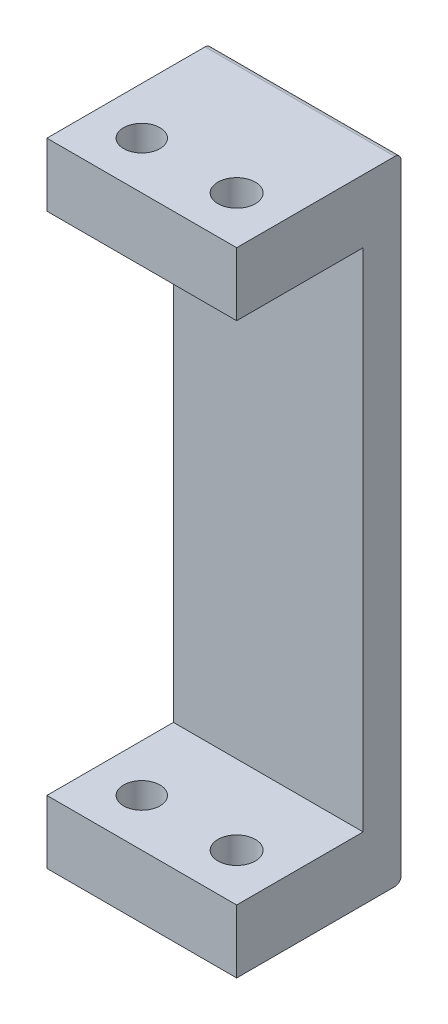
SolidWorks part; units mm, degrees
ref_plane "Front Plane" through (0, 0, 0) normal (0, 0, 1) x (1, 0, 0)
ref_plane "Top Plane" through (0, 0, 0) normal (0, 1, 0) x (1, 0, 0)
ref_plane "Right Plane" through (0, 0, 0) normal (1, 0, 0) x (0, 0, -1)
sketch "Sketch1" plane through (0, 0, 0) normal (0, 0, 1) x (1, 0, 0)
  line L1 (0, 0) -> (150, 0)
  line L2 (0, 0) -> (0, 500)
  line L3 (0, 500) -> (150, 500)
  line L4 (150, 0) -> (150, 500)
  dimension "D1" = 500
  dimension "D2" = 150
extrude "Boss-Extrude1" add sketch "Sketch1" along normal blind 30
sketch "Sketch2" plane through (0, 0, 0) normal (-1, 0, 0) x (0, 0, 1)
  line L0 (30, 500) -> (130, 500)
  line L1 (130, 500) -> (130, 450)
  line L2 (130, 450) -> (30, 450)
  line L3 (30, 500) -> (30, 0) construction
  line L4 (30, 450) -> (30, 500)
extrude "Boss-Extrude2" add sketch "Sketch2" against normal blind 150 contours L4 L0 L1 L2
sketch "Sketch3" plane through (0, 0, 0) normal (-1, 0, 0) x (0, 0, 1)
  line L0 (30, 0) -> (130, 0)
  line L1 (130, 0) -> (130, 50)
  line L2 (130, 50) -> (30, 50)
  line L3 (30, 450) -> (30, 0) construction
  line L4 (30, 50) -> (30, 0)
extrude "Boss-Extrude3" add sketch "Sketch3" against normal blind 150
fillet "Fillet1" radius 5 2 edges at (75, 500, 0) (75, 0, 0)
sketch "Sketch4" plane through (0, 500, 0) normal (0, 1, 0) x (1, 0, 0)
  line L2 (0, -130) -> (0, -5) construction
  line L3 (150, -130) -> (0, -130) construction
  line L4 (150, -130) -> (150, -5) construction
  circle A0 centre (37.5, -92.5) radius 14.3831
  circle A1 centre (112.5, -92.5) radius 14.8146
  dimension "D1" = 37.5
  dimension "D4" = 37.5
  dimension "D2" = 37.5
  dimension "D3" = 37.5
extrude "Cut-Extrude1" cut sketch "Sketch4" against normal through all contours A0 | A1
